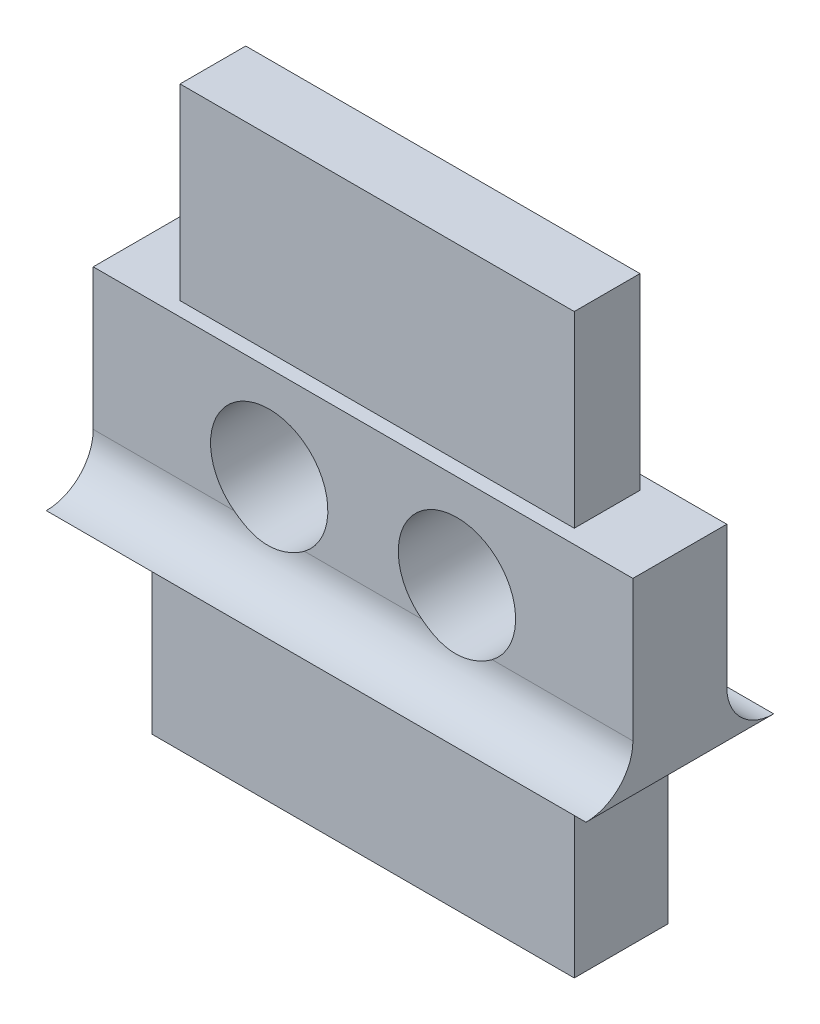
SolidWorks part; units mm, degrees
ref_plane "Front Plane" through (0, 0, 0) normal (0, 0, 1) x (1, 0, 0)
ref_plane "Top Plane" through (0, 0, 0) normal (0, 1, 0) x (1, 0, 0)
ref_plane "Right Plane" through (0, 0, 0) normal (1, 0, 0) x (0, 0, -1)
sketch "Model" plane through (0, 0, 0) normal (0, 0, 1) x (1, 0, 0)
  line L0 (5.7504, 12) -> (5.7504, 0) construction
  line L37 (1.25, 4) -> (0, 4)
  line L38 (10.2507, 4) -> (11.5007, 4)
  line L39 (1.25, 0) -> (10.2507, 0)
  line L40 (1.25, 4) -> (1.25, 0)
  line L41 (10.2507, 4) -> (10.2507, 0)
  line L126 (10.2507, 8) -> (11.5007, 8)
  line L127 (1.25, 8) -> (0, 8)
  line L128 (10.2507, 12) -> (1.25, 12)
  line L129 (10.2507, 8) -> (10.2507, 12)
  line L130 (1.25, 8) -> (1.25, 12)
  line L131 (0, 8) -> (0, 4)
  line L132 (11.5007, 8) -> (11.5007, 4)
  circle A81 centre (7.7507, 6) radius 1.25
  circle A82 centre (3.75, 6) radius 1.25
  dimension "D1" = 2.5
  dimension "D4" = 9.0007
  dimension "D5" = 4
  dimension "D2" = 2
  dimension "D3" = 2.5
  dimension "D6" = 2.5
extrude "Boss-Extrude1" add sketch "Model" along normal blind 2
sketch "Sketch1" plane through (0, 0, 0) normal (-1, 0, 0) x (0, 0, 1)
  line L0 (1, 0) -> (1, 7) construction
  line L1 (2, 4) -> (2, 5)
  line L2 (2, 4) -> (3, 4)
  line L3 (0, 4) -> (-1, 4)
  line L4 (0, 4) -> (0, 5)
  arc A0 (2, 5) -> (3, 4) centre (3, 5) ccw
  arc A1 (0, 5) -> (-1, 4) centre (-1, 5) cw
  dimension "D1" = 1
  dimension "D2" = 1
  dimension "D3" = 4
  dimension "D4" = 1
  dimension "D5" = 2
extrude "Boss-Extrude2" add sketch "Sketch1" against normal up to surface (11.5007 mm away) up to face at (11.5007, 6, 1)
sketch "Sketch2" plane through (0, 0, 2) normal (0, 0, 1) x (1, 0, 0)
  line L0 (5.7504, 12) -> (5.7504, 0) construction
  line L1 (10.2507, 12) -> (1.25, 12) construction
  line L2 (1.25, 0) -> (10.2507, 0) construction
  circle A0 centre (3.75, 6) radius 1.25
  circle A1 centre (7.7507, 6) radius 1.25
  dimension "D1" = 2.5
extrude "Cut-Extrude1" cut sketch "Sketch2" against normal through all both and the other way through all
sketch "Sketch3" plane through (0, 12, 0) normal (0, 1, 0) x (1, 0, 0)
  line L1 (10.2507, 0) -> (1.25, 0)
  line L2 (10.2507, 0) -> (10.2507, -2)
  line L3 (10.2507, -2) -> (1.25, -2)
  line L4 (1.25, 0) -> (1.25, -2)
  line L5 (9.9507, -0.3) -> (1.55, -0.3)
  line L6 (9.9507, -0.3) -> (9.9507, -1.7)
  line L7 (9.9507, -1.7) -> (1.55, -1.7)
  line L8 (1.55, -0.3) -> (1.55, -1.7)
  dimension "D1" = 0.3
  dimension "D2" = 0.3
  dimension "D3" = 0.3
  dimension "D4" = 0.3
extrude "Cut-Extrude2" cut sketch "Sketch3" against normal blind 4
equation "\"D4@Model\"= \"fingerWidth@parametersSketch@prostheticParameters.SLDPRT\" * 0.5556"
equation "\"D2@Sketch3\"=\"tol2@parametersSketch@prostheticParameters.SLDPRT\""
equation "\"D1@Sketch3\"=\"tol2@parametersSketch@prostheticParameters.SLDPRT\""
equation "\"D3@Sketch3\"=\"tol2@parametersSketch@prostheticParameters.SLDPRT\""
equation "\"D4@Sketch3\"=\"tol2@parametersSketch@prostheticParameters.SLDPRT\""
